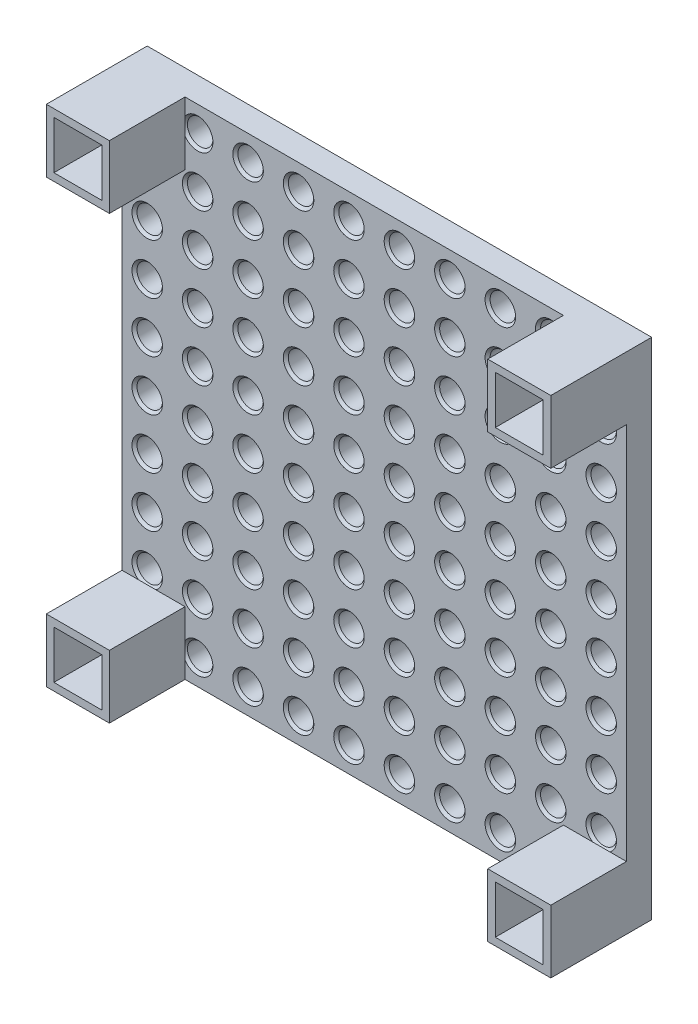
SolidWorks part; units mm, degrees
ref_plane "Front Plane" through (0, 0, 0) normal (0, 0, 1) x (1, 0, 0)
ref_plane "Top Plane" through (0, 0, 0) normal (0, 1, 0) x (1, 0, 0)
ref_plane "Right Plane" through (0, 0, 0) normal (1, 0, 0) x (0, 0, -1)
sketch "Sketch1" plane through (0, 0, 0) normal (0, 0, 1) x (1, 0, 0)
  line L1 (-100, -100) -> (100, -100)
  line L2 (-100, -100) -> (-100, 100)
  line L3 (-100, 100) -> (100, 100)
  line L4 (100, -100) -> (100, 100)
  line L5 (-100, -100) -> (100, 100) construction
  line L6 (-100, 100) -> (100, -100) construction
  point P0 (0, 0)
  dimension "D1" = 200
  dimension "D2" = 200
extrude "Boss-Extrude1" add sketch "Sketch1" along normal blind 10
sketch "Sketch2" plane through (0, 0, 10) normal (0, 0, 1) x (1, 0, 0)
  line L0 (100, 100) -> (-100, 100) construction
  line L1 (-100, 100) -> (-100, -100) construction
  circle A0 centre (-90, 90) radius 5.05
  dimension "D1" = 10.1
  dimension "D2" = 10
  dimension "D3" = 10
extrude "Cut-Extrude1" cut sketch "Sketch2" against normal blind 10
chamfer "Chamfer1" distance 1 angle 45 2 edges at (-84.95, 90, 0) (-84.95, 90, 10)
pattern_linear "LPattern2" count 10 spacing 20 along (1, 0, 0) count 10 spacing 20 along (0, -1, 0) of "Chamfer1", "Cut-Extrude1"
sketch "Sketch3" plane through (0, 0, 10) normal (0, 0, 1) x (1, 0, 0)
  line L0 (-97, 78) -> (-78, 78)
  line L1 (-100, 100) -> (-75, 100)
  line L2 (-100, 100) -> (-100, 75)
  line L3 (-100, 75) -> (-75, 75)
  line L4 (-75, 100) -> (-75, 75)
  line L5 (-78, 97) -> (-78, 78)
  line L6 (-97, 97) -> (-78, 97)
  line L7 (-97, 97) -> (-97, 78)
  dimension "D1" = 25
  dimension "D2" = 25
  dimension "D3" = 3
extrude "Boss-Extrude2" add sketch "Sketch3" along normal blind 30
pattern_linear "LPattern4" count 2 spacing 175 along (1, 0, 0) count 2 spacing 175 along (0, -1, 0) of "Boss-Extrude2"
